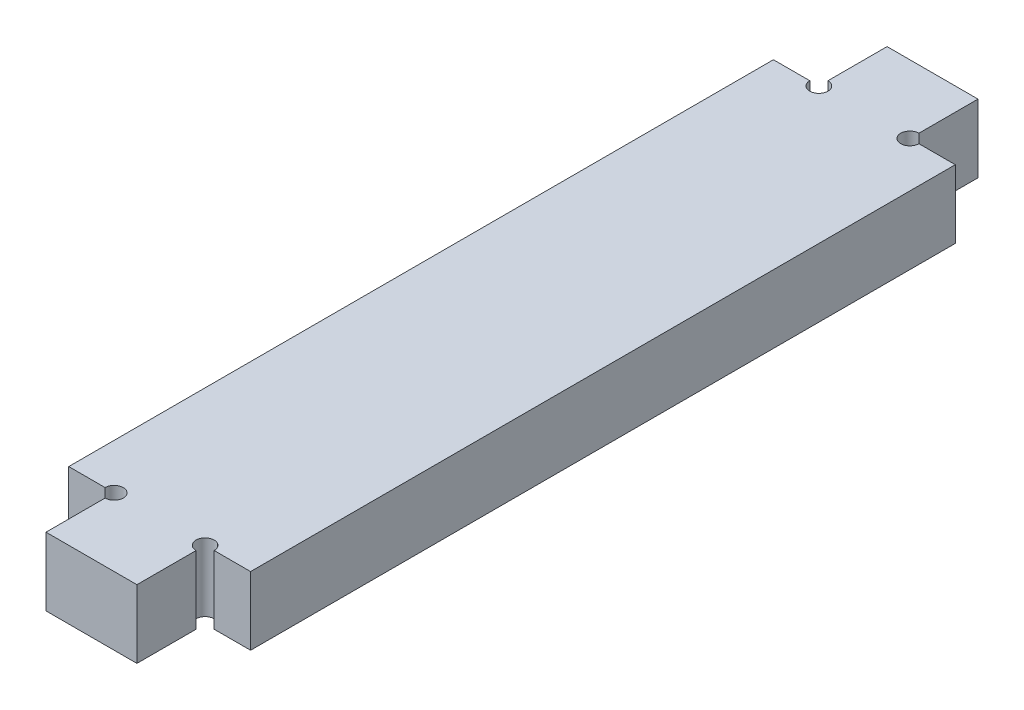
SolidWorks part; units mm, degrees
ref_plane "Front Plane" through (0, 0, 0) normal (0, 0, 1) x (1, 0, 0)
ref_plane "Top Plane" through (0, 0, 0) normal (0, 1, 0) x (1, 0, 0)
ref_plane "Right Plane" through (0, 0, 0) normal (1, 0, 0) x (0, 0, -1)
sketch "Sketch1" plane through (0, 0, 0) normal (0, 1, 0) x (1, 0, 0)
  line L0 (0, 18.5) -> (0, -18.5) construction
  line L1 (-4, 0) -> (4, 0) construction
  line L2 (4, 15.5) -> (4, -15.5)
  line L3 (4, 15.5) -> (2, 15.5)
  line L4 (2, 15.5) -> (2, 18.5)
  line L5 (2, 18.5) -> (-2, 18.5)
  line L6 (-4, 15.5) -> (-2, 15.5)
  line L7 (-4, 15.5) -> (-4, -15.5)
  line L8 (-2, 15.5) -> (-2, 18.5)
  line L9 (-2, -15.5) -> (-2, -18.5)
  line L10 (-4, -15.5) -> (-2, -15.5)
  line L11 (2, -18.5) -> (-2, -18.5)
  line L12 (2, -15.5) -> (2, -18.5)
  line L13 (4, -15.5) -> (2, -15.5)
  dimension "D1" = 3
  dimension "D2" = 2
  dimension "D3" = 2
  dimension "D4" = 15.5
extrude "Boss-Extrude2" add sketch "Sketch1" along normal blind 3
sketch "Sketch4" plane through (0, 3, 0) normal (0, 1, 0) x (1, 0, 0)
  line L0 (2, 15.5) -> (2, 18.5) construction
  line L1 (4, 15.5) -> (2, 15.5) construction
  line L2 (2, 15.9) -> (2, 15.5)
  line L3 (2, 15.5) -> (2.4, 15.5)
  line L4 (0, 18.5) -> (0, -18.5) construction
  line L5 (2, 18.5) -> (-2, 18.5) construction
  line L6 (-2, -18.5) -> (2, -18.5) construction
  line L7 (-4, 0) -> (4, 0) construction
  line L8 (-4, 15.5) -> (-4, -15.5) construction
  line L9 (4, -15.5) -> (4, 15.5) construction
  line L10 (-2, 15.5) -> (-2.4, 15.5)
  line L11 (-2, 15.9) -> (-2, 15.5)
  line L12 (-2, -15.9) -> (-2, -15.5)
  line L13 (-2, -15.5) -> (-2.4, -15.5)
  line L14 (2, -15.5) -> (2.4, -15.5)
  line L15 (2, -15.9) -> (2, -15.5)
  arc A0 (2, 15.9) -> (2.4, 15.5) centre (2, 15.5) ccw
  arc A1 (-2, 15.9) -> (-2.4, 15.5) centre (-2, 15.5) cw
  arc A2 (-2, -15.9) -> (-2.4, -15.5) centre (-2, -15.5) ccw
  arc A3 (2, -15.9) -> (2.4, -15.5) centre (2, -15.5) cw
  dimension "D1" = 0.4
extrude "Cut-Extrude5" cut sketch "Sketch4" against normal blind 3
